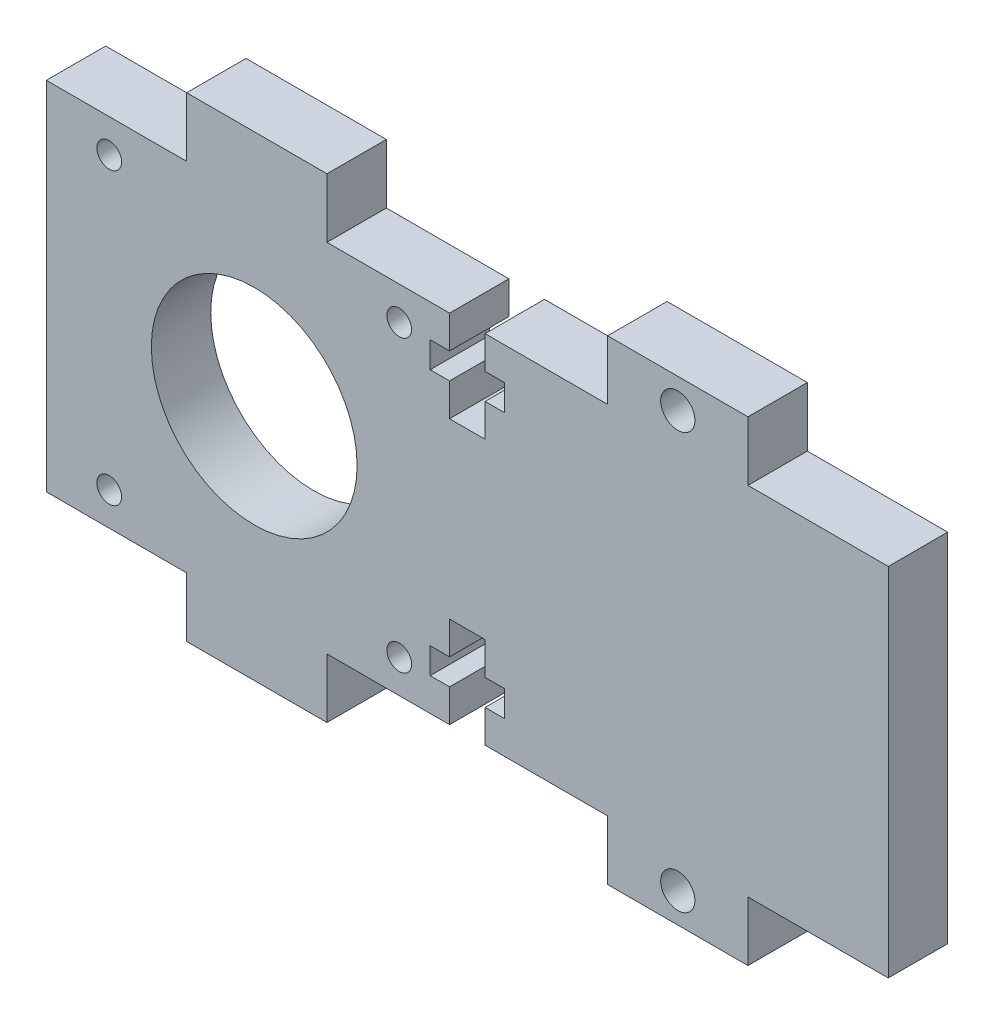
SolidWorks part; units mm, degrees
material "Beech"
ref_plane "Front Plane" through (0, 0, 0) normal (0, 0, 1) x (1, 0, 0)
ref_plane "Top Plane" through (0, 0, 0) normal (0, 1, 0) x (1, 0, 0)
ref_plane "Right Plane" through (0, 0, 0) normal (1, 0, 0) x (0, 0, -1)
sketch "Sketch1" plane through (0, 0, 0) normal (0, 0, 1) x (1, 0, 0)
  line L1 (-45, -25.4) -> (45, -25.4)
  line L2 (-45, -25.4) -> (-45, 25.4)
  line L3 (-45, 25.4) -> (45, 25.4)
  line L4 (45, -25.4) -> (45, 25.4)
  line L5 (-45, -25.4) -> (45, 25.4) construction
  line L6 (-45, 25.4) -> (45, -25.4) construction
  point P0 (0, 0)
  dimension "D1" = 90
  dimension "D2" = 50.8
extrude "Boss-Extrude1" add sketch "Sketch1" along normal blind 6.35
sketch "Sketch2" plane through (0, 0, 6.35) normal (0, 0, 1) x (1, 0, 0)
  line L0 (-45, -25.4) -> (45, -25.4) construction
  line L1 (-45, -25.4) -> (-45, -19.05)
  line L2 (-45, 25.4) -> (-45, -25.4) construction
  line L4 (-30, -25.4) -> (-30, -19.05)
  line L6 (-15, -25.4) -> (-15, -19.05)
  line L8 (15, -25.4) -> (15, -19.05)
  line L10 (30, -25.4) -> (30, -19.05)
  line L11 (-45, -19.05) -> (-30, -19.05)
  line L12 (-45, -25.4) -> (-30, -25.4)
  line L14 (-15, -25.4) -> (15, -25.4)
  line L15 (30, -19.05) -> (45, -19.05)
  line L16 (45, -25.4) -> (45, 25.4) construction
  line L17 (45, -19.05) -> (45, -25.4)
  line L18 (45, -25.4) -> (30, -25.4)
  line L26 (-15, -19.05) -> (15, -19.05)
  circle A0 centre (-22.775, 0) radius 7.9375
  dimension "D4" = 15.875
  dimension "D5" = 30
  dimension "D1" = 25.4
  dimension "D2" = 15
  dimension "D3" = 22.225
  dimension "D6" = 15
  dimension "D7" = 6.35
  dimension "D8" = 15
extrude "Cut-Extrude1" cut sketch "Sketch2" against normal blind 6.35
sketch "Sketch9" plane through (0, 0, 6.35) normal (0, 0, 1) x (1, 0, 0)
  line L0 (0, -19.05) -> (0, 0) construction
  line L1 (15, -19.05) -> (-15, -19.05) construction
  line L2 (-1.8986, -9.271) -> (1.8986, -9.271)
  line L3 (-1.8986, -19.05) -> (-1.8986, -15.5496)
  line L4 (-1.8986, -15.5496) -> (-3.9688, -15.5496)
  line L5 (-3.9688, -15.5496) -> (-3.9688, -12.7714)
  line L6 (-3.9688, -12.7714) -> (-1.8986, -12.7714)
  line L7 (-1.8986, -12.7714) -> (-1.8986, -9.271)
  line L8 (1.8986, -12.7714) -> (1.8986, -9.271)
  line L9 (3.9688, -12.7714) -> (1.8986, -12.7714)
  line L10 (3.9688, -15.5496) -> (3.9688, -12.7714)
  line L11 (1.8986, -15.5496) -> (3.9688, -15.5496)
  line L12 (1.8987, -19.05) -> (1.8986, -15.5496)
  line L13 (-1.8986, -19.05) -> (1.8987, -19.05)
  point P7 (0, -9.271)
  dimension "D1" = 3.7973
  dimension "D2" = 9.779
  dimension "D3" = 2.7781
  dimension "D4" = 3.9688
extrude "Cut-Extrude3" cut sketch "Sketch9" against normal through all
mirror "Mirror2" about plane through (0, 0, 0) normal (0, 1, 0) of "Cut-Extrude3", "Cut-Extrude1"
hole_wizard "#8 Clearance Hole1" [suppressed] positions "Sketch5" profile "Sketch6" hole size "#8" standard "ANSI Inch"
sketch "Sketch5" plane through (0, 0, 6.35) normal (0, 0, 1) x (1, 0, 0)
  line L0 (-34.6812, 0) -> (-10.8687, 0) construction
  circle A0 centre (-22.775, 0) radius 7.9375 construction
  circle A1 centre (-22.775, 0) radius 7.9375 construction
  point P1 (-34.6812, 0)
  point P2 (-10.8687, 0)
  dimension "D1" = 23.8125
sketch "Sketch6" plane through (-34.6812, 0, 6.35) normal (1, 0, 0) x (0, -1, 0)
  line L0 (0, 0) -> (0, 6.35)
  line L1 (0, 6.35) -> (2.1526, 6.35)
  line L2 (2.1526, 6.35) -> (2.1526, 0)
  line L5 (2.1526, 0) -> (0, 0)
  line L11 (0, -6.35) -> (0, 107.95) construction
  dimension "Thru Hole Dia." = 4.3053
  dimension "Thru Hole Depth" = 6.35
sketch "Sketch3" plane through (0, 0, 6.35) normal (0, 0, 1) x (1, 0, 0)
  line L1 (-38.275, -15.5) -> (-7.275, -15.5) construction
  line L2 (-38.275, -15.5) -> (-38.275, 15.5) construction
  line L3 (-38.275, 15.5) -> (-7.275, 15.5) construction
  line L4 (-7.275, -15.5) -> (-7.275, 15.5) construction
  line L5 (-38.275, -15.5) -> (-7.275, 15.5) construction
  line L6 (-38.275, 15.5) -> (-7.275, -15.5) construction
  circle A0 centre (-22.775, 0) radius 11
  circle A1 centre (-38.275, 15.5) radius 1.3208
  circle A2 centre (-7.275, 15.5) radius 1.3208
  circle A3 centre (-7.275, -15.5) radius 1.3208
  circle A4 centre (-38.275, -15.5) radius 1.3208
  dimension "D1" = 22
  dimension "D3" = 2.6416
  dimension "D2" = 31
extrude "Cut-Extrude2" cut sketch "Sketch3" against normal through all
hole_wizard "#6 Clearance Hole1" positions "Sketch10" profile "Sketch11" hole size "#6" standard "ANSI Inch" end condition up to next
sketch "Sketch10" plane through (0, 0, 6.35) normal (0, 0, 1) x (1, 0, 0)
  line L0 (15, -22.225) -> (30, -22.225) construction
  line L3 (30, -19.05) -> (30, -25.4) construction
  line L4 (15, -25.4) -> (15, -19.05) construction
  point P9 (22.5, -22.225)
sketch "Sketch11" plane through (22.5, -22.225, 6.35) normal (1, 0, 0) x (0, -1, 0)
  line L0 (0, 0) -> (0, 6.351)
  line L1 (0, 6.351) -> (1.8288, 6.351)
  line L2 (1.8288, 6.351) -> (1.8288, 0)
  line L5 (1.8288, 0) -> (0, 0)
  line L11 (0, -6.35) -> (0, 107.95) construction
  dimension "Thru Hole Dia." = 3.6576
  dimension "Thru Hole Depth" = 6.351
mirror "Mirror3" about plane through (0, 0, 0) normal (0, 1, 0) of "#6 Clearance Hole1"
mirror "Mirror4" [suppressed] about plane through (0, 0, 0) normal (1, 0, 0)
